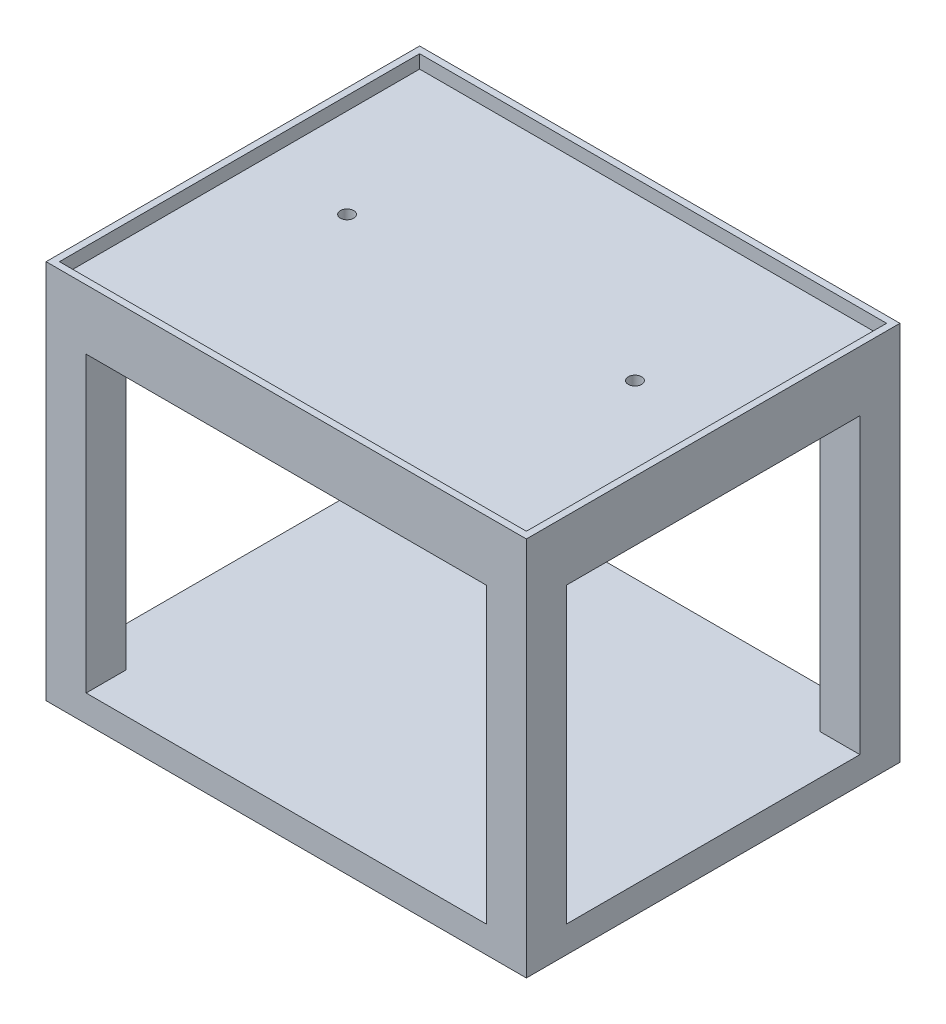
SolidWorks part; units mm, degrees
material "Pine"
ref_plane "Front Plane" through (0, 0, 0) normal (0, 0, 1) x (1, 0, 0)
ref_plane "Top Plane" through (0, 0, 0) normal (0, 1, 0) x (1, 0, 0)
ref_plane "Right Plane" through (0, 0, 0) normal (1, 0, 0) x (0, 0, -1)
sketch "Sketch1" plane through (0, 0, 0) normal (0, 1, 0) x (1, 0, 0)
  line L1 (457.2, -355.6) -> (-457.2, -355.6)
  line L2 (457.2, -355.6) -> (457.2, 355.6)
  line L3 (457.2, 355.6) -> (-457.2, 355.6)
  line L4 (-457.2, -355.6) -> (-457.2, 355.6)
  line L5 (457.2, -355.6) -> (-457.2, 355.6) construction
  line L6 (457.2, 355.6) -> (-457.2, -355.6) construction
  point P0 (0, 0)
  dimension "D1" = 914.4
  dimension "D2" = 711.2
extrude "Boss-Extrude1" add sketch "Sketch1" along normal blind 114.3
sketch "Sketch2" plane through (0, 114.3, 0) normal (0, 1, 0) x (1, 0, 0)
  line L8 (-444.5, 342.9) -> (-444.5, -342.9)
  line L9 (-444.5, -342.9) -> (444.5, -342.9)
  line L10 (444.5, -342.9) -> (444.5, 342.9)
  line L11 (444.5, 342.9) -> (-444.5, 342.9)
  line L12 (-444.5, 342.9) -> (-444.5, -342.9)
  line L13 (-444.5, -342.9) -> (444.5, -342.9)
  line L14 (444.5, -342.9) -> (444.5, 342.9)
  line L15 (444.5, 342.9) -> (-444.5, 342.9)
  dimension "D1" = 12.7
extrude "Cut-Extrude1" cut sketch "Sketch2" against normal offset from surface (25.4 mm away) 88.9 up to face at (0, 0, 0)
sketch "Sketch3" plane through (0, 0, 0) normal (0, -1, 0) x (1, 0, 0)
  line L0 (0, -55) -> (0, 55) construction
  line L1 (-457.2, 355.6) -> (-381, 355.6)
  line L2 (-457.2, 355.6) -> (-457.2, 279.4)
  line L3 (-457.2, 279.4) -> (-381, 279.4)
  line L4 (-381, 355.6) -> (-381, 279.4)
  line L5 (457.2, 355.6) -> (457.2, 279.4)
  line L6 (457.2, 279.4) -> (381, 279.4)
  line L7 (381, 355.6) -> (381, 279.4)
  line L8 (457.2, 355.6) -> (381, 355.6)
  line L9 (55, 0) -> (-55, 0) construction
  line L10 (457.2, -355.6) -> (381, -355.6)
  line L11 (381, -355.6) -> (381, -279.4)
  line L12 (457.2, -279.4) -> (381, -279.4)
  line L13 (457.2, -355.6) -> (457.2, -279.4)
  line L14 (-381, -355.6) -> (-381, -279.4)
  line L15 (-457.2, -279.4) -> (-381, -279.4)
  line L16 (-457.2, -355.6) -> (-457.2, -279.4)
  line L17 (-457.2, -355.6) -> (-381, -355.6)
  dimension "D1" = 76.2
extrude "Boss-Extrude2" add sketch "Sketch3" along normal blind 609.6
sketch "Sketch4" plane through (0, -609.6, 0) normal (0, -1, 0) x (1, 0, 0)
  line L1 (-457.2, 355.6) -> (457.2, 355.6)
  line L2 (-457.2, 355.6) -> (-457.2, -355.6)
  line L3 (-457.2, -355.6) -> (457.2, -355.6)
  line L4 (457.2, 355.6) -> (457.2, -355.6)
extrude "Boss-Extrude3" add sketch "Sketch4" against normal blind 50.8
hole_wizard "1 (1) Diameter Hole1" positions "Sketch5" profile "Sketch6" hole size "1" standard "ANSI Inch"
sketch "Sketch5" plane through (0, 88.9, 0) normal (0, 1, 0) x (1, 0, 0)
  line L0 (-274.0281, 34.3) -> (274.0281, 34.3) construction
  point P0 (-274.0281, 34.3)
  point P2 (274.0281, 34.3)
  point P17 (0, 34.3)
  dimension "D1" = 548.0563
  dimension "D2" = 34.3
sketch "Sketch6" plane through (-274.0281, 88.9, -34.3) normal (1, 0, 0) x (0, 0, 1)
  line L0 (0, 0) -> (0, 88.9)
  line L1 (0, 88.9) -> (12.7, 88.9)
  line L2 (12.7, 88.9) -> (12.7, 0)
  line L5 (12.7, 0) -> (0, 0)
  line L11 (0, -6.35) -> (0, 107.95) construction
  dimension "Thru Hole Dia." = 25.4
  dimension "Thru Hole Depth" = 88.9
